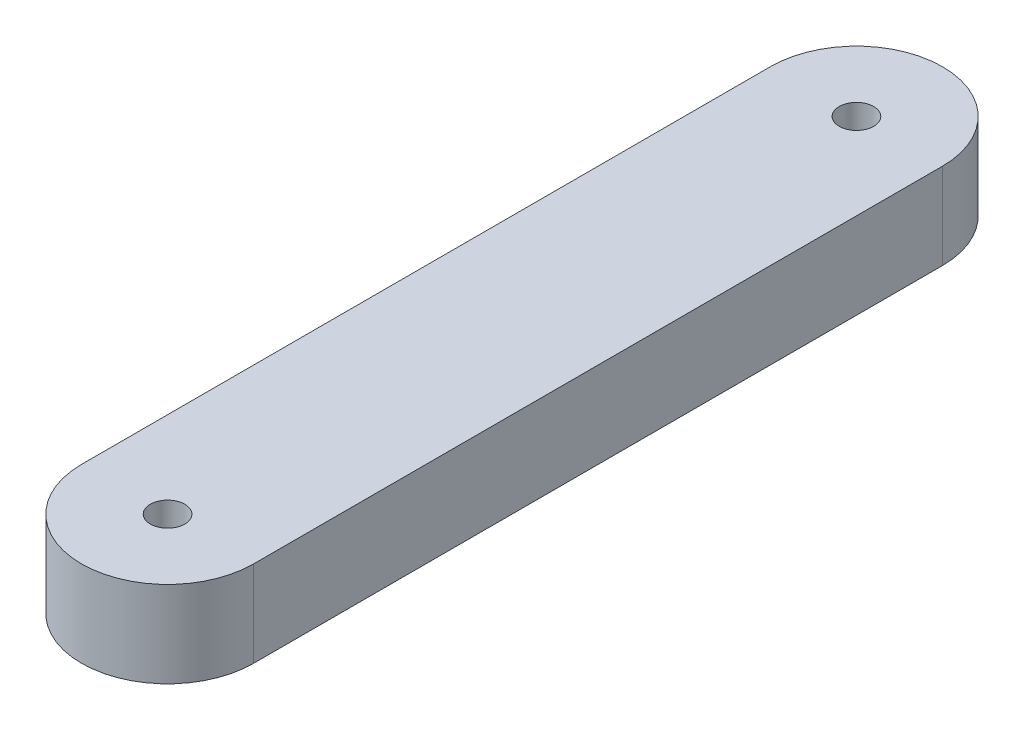
SolidWorks part; units mm, degrees
ref_plane "Front Plane" through (0, 0, 0) normal (0, 0, 1) x (1, 0, 0)
ref_plane "Top Plane" through (0, 0, 0) normal (0, 1, 0) x (1, 0, 0)
ref_plane "Right Plane" through (0, 0, 0) normal (1, 0, 0) x (0, 0, -1)
sketch "Sketch2" plane through (0, 0, 0) normal (0, 1, 0) x (1, 0, 0)
  line L0 (-5, 40) -> (-5, 0)
  line L1 (5, 40) -> (5, 0)
  arc A0 (-5, 0) -> (5, 0) centre (0, 0) ccw
  circle A1 centre (0, 0) radius 1
  arc A2 (5, 40) -> (-5, 40) centre (0, 40) ccw
  circle A3 centre (0, 40) radius 1
  dimension "D1" = 10
  dimension "D2" = 10
  dimension "D3" = 2
  dimension "D4" = 2
  dimension "D5" = 40
extrude "Boss-Extrude1" add sketch "Sketch2" along normal blind 5
